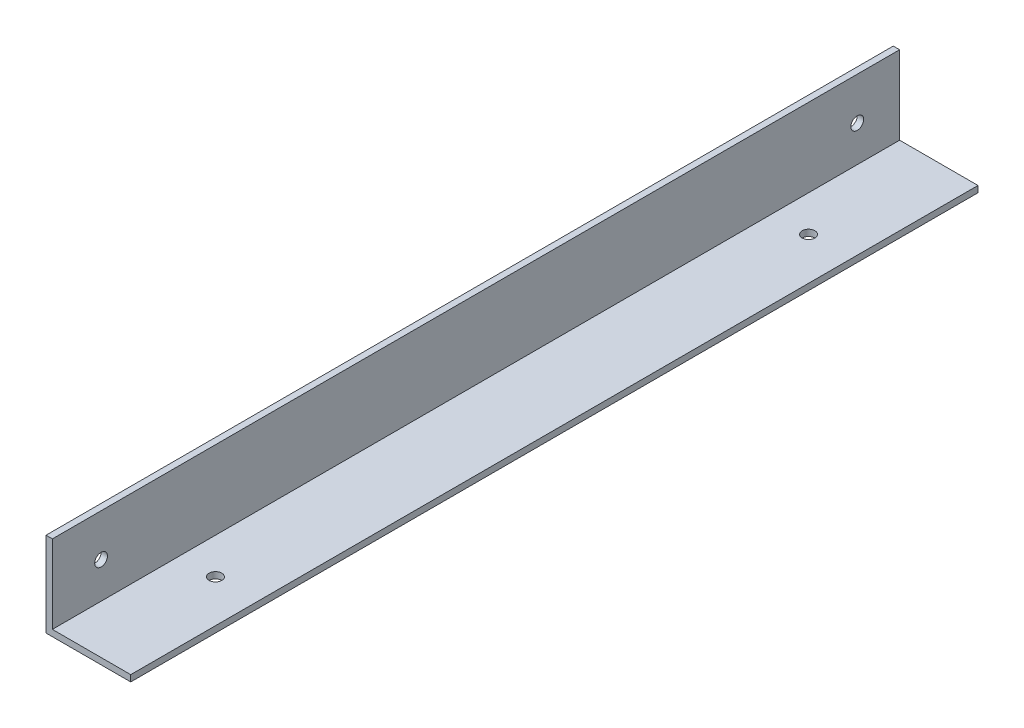
SolidWorks part; units mm, degrees
ref_plane "Plan de face" through (0, 0, 0) normal (0, 0, 1) x (1, 0, 0)
ref_plane "Plan de dessus" through (0, 0, 0) normal (0, 1, 0) x (1, 0, 0)
ref_plane "Plan de droite" through (0, 0, 0) normal (1, 0, 0) x (0, 0, -1)
sketch "Esquisse1" plane through (0, 0, 0) normal (0, 0, 1) x (1, 0, 0)
  line L0 (-18.1135, 1.8189) -> (-18.1135, -18.1811)
  line L1 (-18.1135, -18.1811) -> (1.8865, -18.1811)
  line L2 (1.8865, -18.1811) -> (1.8865, -16.6811)
  line L3 (1.8865, -16.6811) -> (-16.6135, -16.6811)
  line L4 (-16.6135, -16.6811) -> (-16.6135, 1.8189)
  line L5 (-16.6135, 1.8189) -> (-18.1135, 1.8189)
  dimension "D1" = 1.5
  dimension "D2" = 1.5
  dimension "D3" = 20
  dimension "D4" = 20
extrude "Extrusion1" add sketch "Esquisse1" along normal blind 200
sketch "Esquisse2" plane through (0, -16.6811, 0) normal (0, 1, 0) x (-1, 0, 0)
  line L1 (18.1135, 200) -> (-1.8865, 200) construction
  line L2 (18.1135, 0) -> (-1.8865, 0) construction
  line L5 (8.1135, 170) -> (8.1135, 30) construction
  line L7 (-1.8865, 200) -> (-1.8865, 0) construction
  circle A0 centre (8.1135, 170) radius 1.5
  circle A1 centre (8.1135, 30) radius 1.5
  point P2 (8.1135, 0)
  dimension "D2" = 30
  dimension "D1" = 30
  dimension "D3" = 10
sketch "Esquisse3" plane through (-16.6135, 0, 0) normal (1, 0, 0) x (0, 0, -1)
  line L0 (-188.5, -8.1811) -> (-10, -8.1811) construction
  line L1 (-200, -16.6811) -> (-200, 1.8189) construction
  line L2 (0, -16.6811) -> (0, 1.8189) construction
  line L3 (-200, 1.8189) -> (0, 1.8189) construction
  circle A0 centre (-10, -8.1811) radius 1.5
  circle A1 centre (-188.5, -8.1811) radius 1.5
  dimension "D1" = 10
  dimension "D2" = 11.5
  dimension "D3" = 10
extrude "Extrusion3" cut sketch "Esquisse3" against normal blind 150
extrude "Extrusion4" cut sketch "Esquisse2" against normal blind 100
